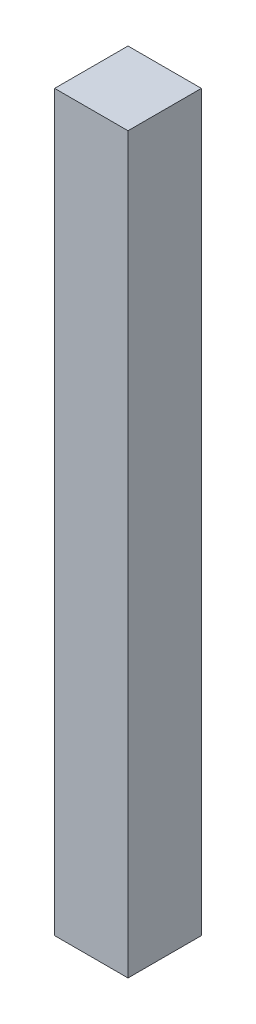
SolidWorks part; units mm, degrees
ref_plane "Ebene vorne" through (0, 0, 0) normal (0, 0, 1) x (1, 0, 0)
ref_plane "Ebene oben" through (0, 0, 0) normal (0, 1, 0) x (1, 0, 0)
ref_plane "Ebene rechts" through (0, 0, 0) normal (1, 0, 0) x (0, 0, -1)
sketch "Skizze1" plane through (0, 0, 0) normal (0, 1, 0) x (1, 0, 0)
  line L1 (-37.5, -37.5) -> (37.5, -37.5)
  line L2 (-37.5, -37.5) -> (-37.5, 37.5)
  line L3 (-37.5, 37.5) -> (37.5, 37.5)
  line L4 (37.5, -37.5) -> (37.5, 37.5)
  line L5 (-37.5, -37.5) -> (37.5, 37.5) construction
  line L6 (-37.5, 37.5) -> (37.5, -37.5) construction
  point P0 (0, 0)
  dimension "D1" = 75
  dimension "D2" = 75
extrude "Aufsatz-Linear austragen1" add sketch "Skizze1" along normal blind 750
